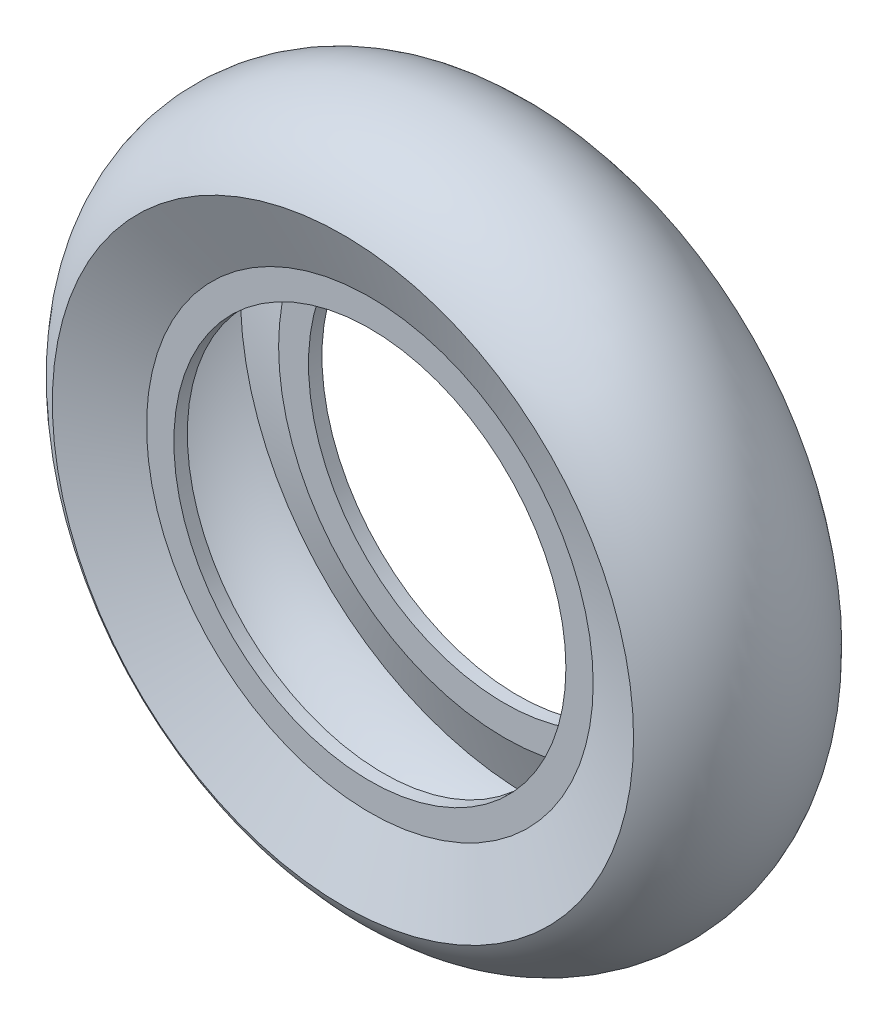
SolidWorks part; units mm, degrees
material "VITON"
ref_plane "Front Plane" through (0, 0, 0) normal (0, 0, 1) x (1, 0, 0)
ref_plane "Top Plane" through (0, 0, 0) normal (0, 1, 0) x (1, 0, 0)
ref_plane "Right Plane" through (0, 0, 0) normal (1, 0, 0) x (0, 0, -1)
sketch "Sketch1" plane through (-82.316, -44.5258, 136.6528) normal (1, 0, 0) x (0, 0, -1)
  line L0 (0, 0) -> (55.642, 0) construction
  line L1 (0, 52.6641) -> (6.35, 68.5391)
  line L2 (-34.925, 52.6641) -> (-41.275, 68.5391)
  line L3 (0, 46.228) -> (0, 52.6641)
  line L4 (-34.925, 46.228) -> (-34.925, 52.6641)
  line L5 (-17.4625, 82.55) -> (13.8543, 82.55) construction
  line L6 (-41.275, 68.5391) -> (-34.925, 68.5391) construction
  line L7 (-34.925, 68.5391) -> (-34.925, 52.6641) construction
  line L8 (6.35, 68.5391) -> (0, 68.5391) construction
  line L9 (0, 68.5391) -> (0, 52.6641) construction
  arc A0 (6.35, 68.5391) -> (-41.275, 68.5391) centre (-17.4625, 55.309) ccw
  dimension "D1" = 82.55
  dimension "D3" = 15.875
  dimension "D2" = 6.35
revolve "Revolve-Thin1" add sketch "Sketch1" angle 360 about L0
sketch "Sketch2" plane through (0, 0, 0) normal (0, 0, -1) x (-1, 0, 0)
  line L1 (6.116, -120.7258) -> (158.516, -120.7258)
  line L2 (6.116, -120.7258) -> (6.116, -133.4258)
  line L3 (6.116, -133.4258) -> (158.516, -133.4258)
  line L4 (158.516, -120.7258) -> (158.516, -133.4258)
  point P4 (82.316, -120.7258)
  dimension "D1" = 76.2
  dimension "D2" = 152.4
  dimension "D3" = 12.7
extrude "Cut-Extrude1" cut sketch "Sketch2" against normal through all
sketch "Sketch3" plane through (0, -120.7258, 0) normal (0, -1, 0) x (1, 0, 0)
  spline S1 degree 3 poles (-82.7296, 136.6328) (-80.6618, 136.6328) (-79.0184, 136.6966) (-75.7538, 136.9532) (-74.1324, 137.1459) (-70.9142, 137.6743) (-69.3172, 138.0098) (-66.9441, 138.6432) (-66.1568, 138.8762) (-64.5907, 139.3924) (-63.8104, 139.6762) (-61.4952, 140.6124) (-60.0044, 141.3396) (-57.8761, 142.6417) (-57.1849, 143.1119) (-55.872, 144.1195) (-55.247, 144.6586) (-54.3663, 145.5305) (-54.0822, 145.8317) (-53.5353, 146.458) (-53.2714, 146.7846) (-52.5269, 147.7899) (-52.0915, 148.495) (-51.5453, 149.6136) (-51.381, 149.9973) (-51.0931, 150.7852) (-50.9719, 151.1829) (-50.6772, 152.3873) (-50.5723, 153.2055) (-50.5633, 154.4573) (-50.5857, 154.8788) (-50.6788, 155.7055) (-50.7494, 156.1139) (-50.9366, 156.9212) (-51.0532, 157.32) (-51.3312, 158.1086) (-51.4924, 158.4971) (-52.0288, 159.6254) (-52.4591, 160.3367) (-53.1977, 161.3513) (-53.4585, 161.6792) (-54.0003, 162.3091) (-54.2822, 162.6123) (-55.1574, 163.4906) (-55.7799, 164.0343) (-57.0908, 165.0517) (-57.782, 165.5266) (-59.8976, 166.834) (-61.3752, 167.5618) (-63.6641, 168.4986) (-64.4393, 168.7845) (-66.0117, 169.3096) (-66.8094, 169.5487) (-69.2044, 170.1955) (-70.8129, 170.5367) (-74.0492, 171.0737) (-75.6769, 171.2693) (-78.9496, 171.5304) (-80.5945, 171.596) (-83.0745, 171.5986) (-83.9037, 171.5834) (-85.5532, 171.5207) (-86.375, 171.4734) (-88.8317, 171.2824) (-90.4579, 171.0903) (-93.6844, 170.5629) (-95.2849, 170.2277) (-97.6621, 169.5948) (-98.4506, 169.3619) (-100.0186, 168.8462) (-100.7991, 168.5629) (-103.1181, 167.6269) (-104.6109, 166.8998) (-106.7416, 165.5983) (-107.4343, 165.1278) (-108.7497, 164.1197) (-109.3756, 163.5805) (-110.2574, 162.7087) (-110.5418, 162.4076) (-111.0892, 161.7817) (-111.3533, 161.4554) (-112.1002, 160.4483) (-112.5367, 159.7424) (-113.0838, 158.6234) (-113.2482, 158.2403) (-113.537, 157.4517) (-113.6589, 157.0524) (-113.9546, 155.8457) (-114.0596, 155.0267) (-114.0688, 153.7749) (-114.0465, 153.3526) (-113.9532, 152.5244) (-113.8825, 152.1154) (-113.6949, 151.3073) (-113.5781, 150.9081) (-113.2999, 150.1193) (-113.1382, 149.7301) (-112.6006, 148.6002) (-112.1695, 147.8885) (-111.4301, 146.8737) (-111.1686, 146.5452) (-110.6255, 145.9146) (-110.3431, 145.6111) (-109.4663, 144.7322) (-108.8428, 144.1884) (-107.5304, 143.1711) (-106.8382, 142.696) (-104.7185, 141.3878) (-103.2386, 140.6602) (-100.9472, 139.724) (-100.1712, 139.4383) (-98.5976, 138.9138) (-97.7986, 138.6748) (-95.3986, 138.0283) (-93.7862, 137.6873) (-90.5413, 137.1511) (-88.9088, 136.9562) (-86.4466, 136.7618) (-85.6236, 136.7134) (-84.3858, 136.6651) (-83.9726, 136.653) (-83.1452, 136.6368) (-82.7296, 136.6328) (-80.6618, 136.6328) (-79.0184, 136.6966) knots -0.007813 -0.007813 0 0 0.03125 0.03125 0.0625 0.0625 0.09375 0.09375 0.109375 0.109375 0.125 0.125 0.15625 0.15625 0.171875 0.171875 0.1875 0.1875 0.195312 0.195312 0.203125 0.203125 0.21875 0.21875 0.226562 0.226562 0.234375 0.234375 0.25 0.25 0.257812 0.257812 0.265625 0.265625 0.273437 0.273437 0.28125 0.28125 0.296875 0.296875 0.304687 0.304687 0.3125 0.3125 0.328125 0.328125 0.34375 0.34375 0.375 0.375 0.390625 0.390625 0.40625 0.40625 0.4375 0.4375 0.46875 0.46875 0.5 0.5 0.515625 0.515625 0.53125 0.53125 0.5625 0.5625 0.59375 0.59375 0.609375 0.609375 0.625 0.625 0.65625 0.65625 0.671875 0.671875 0.6875 0.6875 0.695312 0.695312 0.703125 0.703125 0.71875 0.71875 0.726562 0.726562 0.734375 0.734375 0.75 0.75 0.757812 0.757812 0.765625 0.765625 0.773437 0.773437 0.78125 0.78125 0.796875 0.796875 0.804687 0.804687 0.8125 0.8125 0.828125 0.828125 0.84375 0.84375 0.875 0.875 0.890625 0.890625 0.90625 0.90625 0.9375 0.9375 0.96875 0.96875 0.984375 0.984375 0.992187 0.992187 1 1 1.03125 1.03125 1.0625 only from (-82.316, 136.6328) to (-82.316, 136.6328)
  spline S2 degree 3 poles (-82.7296, 136.6328) (-80.6618, 136.6328) (-79.0184, 136.6966) (-75.7538, 136.9532) (-74.1324, 137.1459) (-70.9142, 137.6743) (-69.3172, 138.0098) (-66.9441, 138.6432) (-66.1568, 138.8762) (-64.5907, 139.3924) (-63.8104, 139.6762) (-61.4952, 140.6124) (-60.0044, 141.3396) (-57.8761, 142.6417) (-57.1849, 143.1119) (-55.872, 144.1195) (-55.247, 144.6586) (-54.3663, 145.5305) (-54.0822, 145.8317) (-53.5353, 146.458) (-53.2714, 146.7846) (-52.5269, 147.7899) (-52.0915, 148.495) (-51.5453, 149.6136) (-51.381, 149.9973) (-51.0931, 150.7852) (-50.9719, 151.1829) (-50.6772, 152.3873) (-50.5723, 153.2055) (-50.5633, 154.4573) (-50.5857, 154.8788) (-50.6788, 155.7055) (-50.7494, 156.1139) (-50.9366, 156.9212) (-51.0532, 157.32) (-51.3312, 158.1086) (-51.4924, 158.4971) (-52.0288, 159.6254) (-52.4591, 160.3367) (-53.1977, 161.3513) (-53.4585, 161.6792) (-54.0003, 162.3091) (-54.2822, 162.6123) (-55.1574, 163.4906) (-55.7799, 164.0343) (-57.0908, 165.0517) (-57.782, 165.5266) (-59.8976, 166.834) (-61.3752, 167.5618) (-63.6641, 168.4986) (-64.4393, 168.7845) (-66.0117, 169.3096) (-66.8094, 169.5487) (-69.2044, 170.1955) (-70.8129, 170.5367) (-74.0492, 171.0737) (-75.6769, 171.2693) (-78.9496, 171.5304) (-80.5945, 171.596) (-83.0745, 171.5986) (-83.9037, 171.5834) (-85.5532, 171.5207) (-86.375, 171.4734) (-88.8317, 171.2824) (-90.4579, 171.0903) (-93.6844, 170.5629) (-95.2849, 170.2277) (-97.6621, 169.5948) (-98.4506, 169.3619) (-100.0186, 168.8462) (-100.7991, 168.5629) (-103.1181, 167.6269) (-104.6109, 166.8998) (-106.7416, 165.5983) (-107.4343, 165.1278) (-108.7497, 164.1197) (-109.3756, 163.5805) (-110.2574, 162.7087) (-110.5418, 162.4076) (-111.0892, 161.7817) (-111.3533, 161.4554) (-112.1002, 160.4483) (-112.5367, 159.7424) (-113.0838, 158.6234) (-113.2482, 158.2403) (-113.537, 157.4517) (-113.6589, 157.0524) (-113.9546, 155.8457) (-114.0596, 155.0267) (-114.0688, 153.7749) (-114.0465, 153.3526) (-113.9532, 152.5244) (-113.8825, 152.1154) (-113.6949, 151.3073) (-113.5781, 150.9081) (-113.2999, 150.1193) (-113.1382, 149.7301) (-112.6006, 148.6002) (-112.1695, 147.8885) (-111.4301, 146.8737) (-111.1686, 146.5452) (-110.6255, 145.9146) (-110.3431, 145.6111) (-109.4663, 144.7322) (-108.8428, 144.1884) (-107.5304, 143.1711) (-106.8382, 142.696) (-104.7185, 141.3878) (-103.2386, 140.6602) (-100.9472, 139.724) (-100.1712, 139.4383) (-98.5976, 138.9138) (-97.7986, 138.6748) (-95.3986, 138.0283) (-93.7862, 137.6873) (-90.5413, 137.1511) (-88.9088, 136.9562) (-86.4466, 136.7618) (-85.6236, 136.7134) (-84.3858, 136.6651) (-83.9726, 136.653) (-83.1452, 136.6368) (-82.7296, 136.6328) (-80.6618, 136.6328) (-79.0184, 136.6966) knots -0.007813 -0.007813 0 0 0.03125 0.03125 0.0625 0.0625 0.09375 0.09375 0.109375 0.109375 0.125 0.125 0.15625 0.15625 0.171875 0.171875 0.1875 0.1875 0.195312 0.195312 0.203125 0.203125 0.21875 0.21875 0.226562 0.226562 0.234375 0.234375 0.25 0.25 0.257812 0.257812 0.265625 0.265625 0.273437 0.273437 0.28125 0.28125 0.296875 0.296875 0.304687 0.304687 0.3125 0.3125 0.328125 0.328125 0.34375 0.34375 0.375 0.375 0.390625 0.390625 0.40625 0.40625 0.4375 0.4375 0.46875 0.46875 0.5 0.5 0.515625 0.515625 0.53125 0.53125 0.5625 0.5625 0.59375 0.59375 0.609375 0.609375 0.625 0.625 0.65625 0.65625 0.671875 0.671875 0.6875 0.6875 0.695312 0.695312 0.703125 0.703125 0.71875 0.71875 0.726562 0.726562 0.734375 0.734375 0.75 0.75 0.757812 0.757812 0.765625 0.765625 0.773437 0.773437 0.78125 0.78125 0.796875 0.796875 0.804687 0.804687 0.8125 0.8125 0.828125 0.828125 0.84375 0.84375 0.875 0.875 0.890625 0.890625 0.90625 0.90625 0.9375 0.9375 0.96875 0.96875 0.984375 0.984375 0.992187 0.992187 1 1 1.03125 1.03125 1.0625 only from (-82.316, 136.6328) to (-82.316, 136.6328)
  dimension "D1" = 0
extrude "Boss-Extrude1" add sketch "Sketch3" against normal blind 2.54
